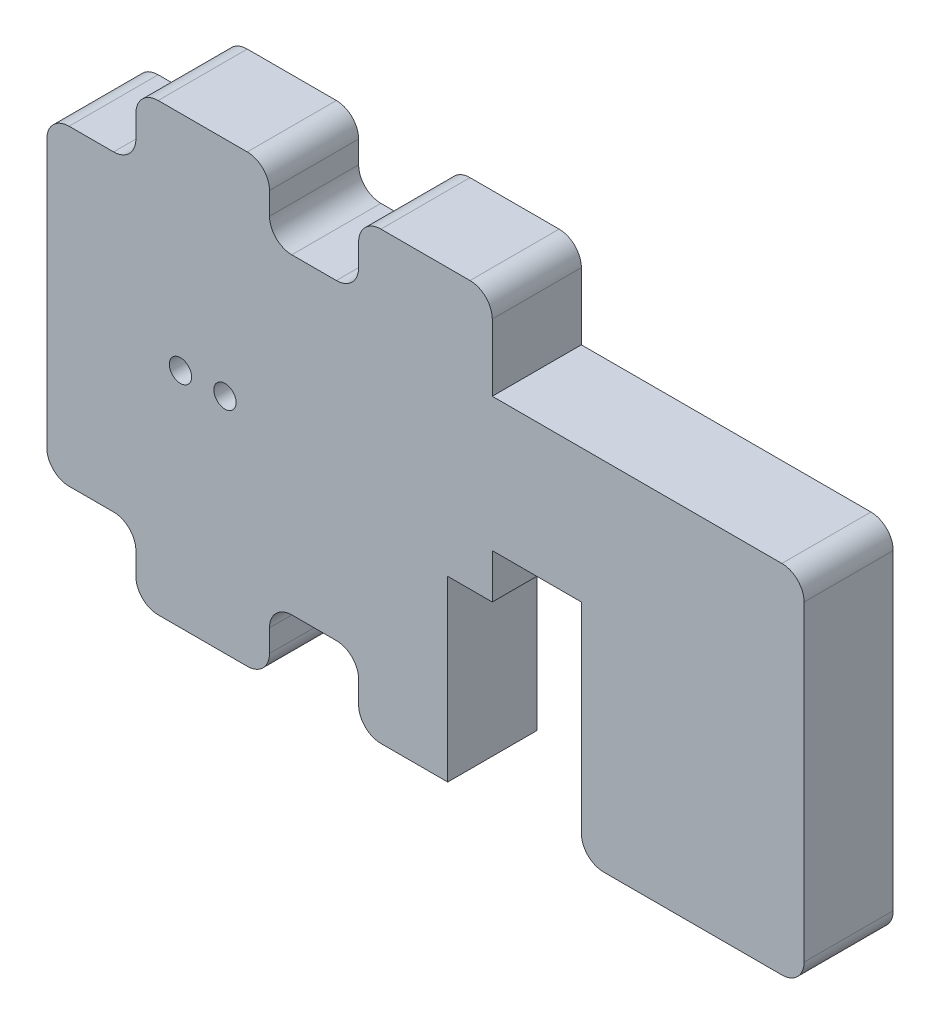
SolidWorks part; units mm, degrees
ref_plane "Front" through (0, 0, 0) normal (0, 0, 1) x (1, 0, 0)
ref_plane "Top" through (0, 0, 0) normal (0, 1, 0) x (1, 0, 0)
ref_plane "Right" through (0, 0, 0) normal (1, 0, 0) x (0, 0, -1)
sketch "Sketch1" plane through (0, 0, 0) normal (0, 0, 1) x (1, 0, 0)
  line L1 (0, 0) -> (38.1, 0)
  line L2 (0, 0) -> (0, 25.4)
  line L3 (0, 25.4) -> (38.1, 25.4)
  line L4 (38.1, 0) -> (38.1, 25.4)
  dimension "D1" = 38.1
  dimension "D2" = 25.4
extrude "Boss-Extrude1" add sketch "Sketch1" along normal blind 5.08
sketch "Sketch2" plane through (0, 0, 5.08) normal (0, 0, 1) x (1, 0, 0)
  line L0 (0, 12.7) -> (38.1, 12.7) construction
  line L3 (17.78, 12.7) -> (20.32, 12.7) construction
  line L4 (19.05, 25.4) -> (19.05, 0) construction
  line L5 (38.1, 25.4) -> (0, 25.4) construction
  line L6 (0, 0) -> (38.1, 0) construction
  line L7 (0, 25.4) -> (0, 0) construction
  line L8 (38.1, 0) -> (38.1, 25.4) construction
  circle A0 centre (17.78, 12.7) radius 0.635
  circle A1 centre (20.32, 12.7) radius 0.635
  point P4 (19.05, 12.7)
  point P16 (8.255, 8.255)
  dimension "D1" = 1.27
  dimension "D2" = 2.54
extrude "Cut-Extrude1" cut sketch "Sketch2" against normal through all and the other way through all
sketch "Sketch3" plane through (0, 0, 0) normal (0, 0, -1) x (-1, 0, 0)
  line L0 (-38.1, 25.4) -> (0, 25.4) construction
  line L1 (-27.94, 25.4) -> (-22.86, 25.4)
  line L2 (-27.94, 25.4) -> (-27.94, 21.59)
  line L3 (-27.94, 21.59) -> (-22.86, 21.59)
  line L4 (-22.86, 25.4) -> (-22.86, 21.59)
  line L6 (-15.24, 25.4) -> (-10.16, 25.4)
  line L7 (-15.24, 25.4) -> (-15.24, 21.59)
  line L8 (-15.24, 21.59) -> (-10.16, 21.59)
  line L9 (-10.16, 25.4) -> (-10.16, 21.59)
  line L14 (-38.1, 0) -> (-38.1, 25.4) construction
  line L19 (0, 25.4) -> (0, 0) construction
  dimension "D1" = 10.16
  dimension "D2" = 5.08
  dimension "D3" = 5.08
  dimension "D4" = 10.16
  dimension "D5" = 3.81
extrude "Cut-Extrude2" cut sketch "Sketch3" against normal through all
ref_plane "Plane1" through (0, 12.7, 0) normal (0, 1, 0) x (1, 0, 0)
mirror "Mirror1" about plane through (0, 12.7, 0) normal (0, 1, 0) of "Cut-Extrude2"
sketch "Sketch4" plane through (0, 0, 5.08) normal (0, 0, 1) x (1, 0, 0)
  line L1 (38.1, 0) -> (35.56, 0)
  line L2 (38.1, 0) -> (38.1, 12.7)
  line L3 (38.1, 12.7) -> (35.56, 12.7)
  line L4 (35.56, 0) -> (35.56, 12.7)
  dimension "D1" = 2.54
  dimension "D2" = 12.7
extrude "Cut-Extrude3" cut sketch "Sketch4" against normal through all
sketch "Sketch5" plane through (0, 0, 5.08) normal (0, 0, 1) x (1, 0, 0)
  line L0 (38.1, 12.7) -> (38.1, 25.4) construction
  line L1 (38.1, 20.32) -> (53.34, 20.32)
  line L2 (38.1, 20.32) -> (38.1, 12.7)
  line L3 (38.1, 12.7) -> (40.64, 12.7)
  line L4 (53.34, 20.32) -> (53.34, 0)
  line L5 (27.94, 0) -> (35.56, 0) construction
  line L8 (53.34, 0) -> (40.64, 0)
  line L9 (40.64, 12.7) -> (40.64, 0)
  line L10 (1.397, 12.7) -> (-1.397, 12.7) construction
  dimension "D1" = 2.54
  dimension "D2" = 12.7
  dimension "D3" = 7.62
extrude "Boss-Extrude2" add sketch "Sketch5" against normal through all
sketch "Sketch6" plane through (0, 0, 5.08) normal (0, 0, 1) x (1, 0, 0)
  line L1 (0, 25.4) -> (10.16, 25.4)
  line L2 (0, 25.4) -> (0, 0)
  line L3 (0, 0) -> (10.16, 0)
  line L4 (10.16, 25.4) -> (10.16, 0)
extrude "Cut-Extrude4" cut sketch "Sketch6" against normal through all
sketch "Sketch7" plane through (0, 0, 5.08) normal (0, 0, 1) x (1, 0, 0)
  line L0 (38.1, 25.4) -> (27.94, 25.4) construction
  line L1 (38.1, 20.32) -> (35.56, 20.32)
  line L2 (38.1, 20.32) -> (38.1, 25.4)
  line L3 (38.1, 25.4) -> (35.56, 25.4)
  line L4 (35.56, 20.32) -> (35.56, 25.4)
  line L5 (35.56, 12.7) -> (35.56, 0) construction
extrude "Cut-Extrude5" cut sketch "Sketch7" against normal through all
fillet "Fillet1" radius 1.27 15 edges at (22.86, 3.81, 2.54) (22.86, 0, 2.54) (27.94, 0, 2.54) (27.94, 3.81, 2.54) (15.24, 0, 2.54) (15.24, 3.81, 2.54) (10.16, 3.81, 2.54) (35.56, 25.4, 2.54) (22.86, 21.59, 2.54) (22.86, 25.4, 2.54) (27.94, 21.59, 2.54) (27.94, 25.4, 2.54) (10.16, 21.59, 2.54) (15.24, 21.59, 2.54) (15.24, 25.4, 2.54)
sketch "Sketch8" plane through (0, 0, 5.08) normal (0, 0, 1) x (1, 0, 0)
  line L1 (35.56, 0) -> (33.02, 0)
  line L2 (35.56, 0) -> (35.56, 10.16)
  line L3 (35.56, 10.16) -> (33.02, 10.16)
  line L4 (33.02, 0) -> (33.02, 10.16)
  dimension "D1" = 2.54
  dimension "D2" = 10.16
extrude "Cut-Extrude6" cut sketch "Sketch8" against normal through all
fillet "Fillet2" radius 1.27 3 edges at (40.64, 0, 2.54) (53.34, 0, 2.54) (53.34, 20.32, 2.54)
